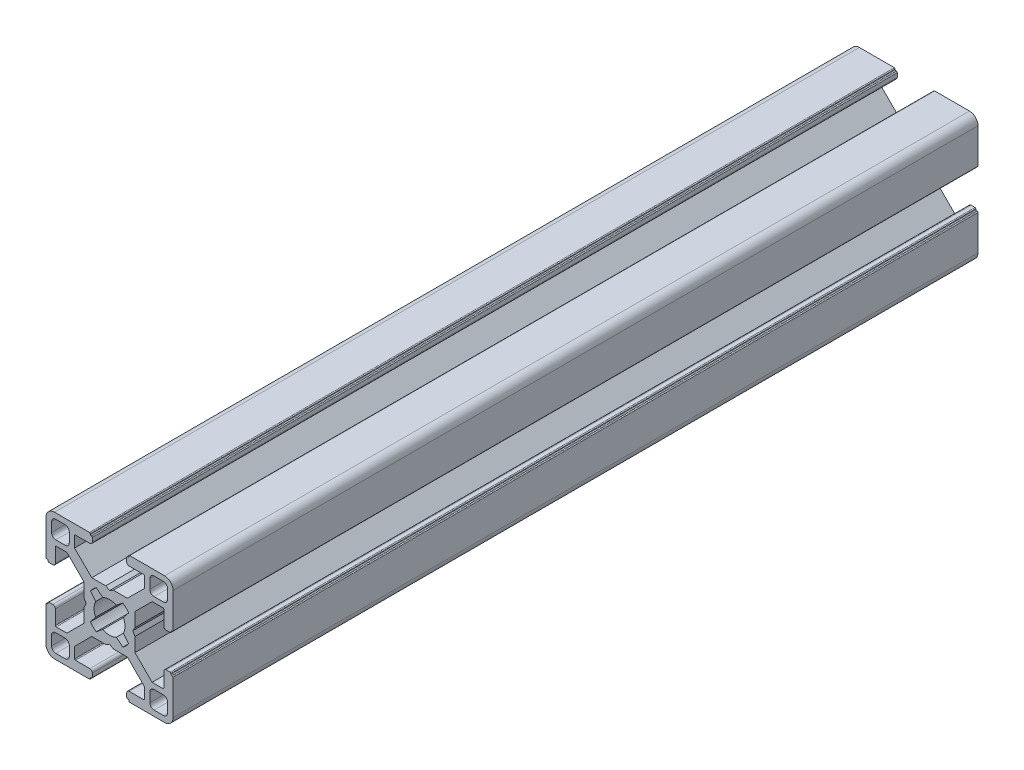
SolidWorks part; units mm, degrees
material "6061 Alloy"
ref_plane "Front" through (0, 0, 0) normal (0, 0, 1) x (1, 0, 0)
ref_plane "Top" through (0, 0, 0) normal (0, 1, 0) x (1, 0, 0)
ref_plane "Right" through (0, 0, 0) normal (1, 0, 0) x (0, 0, -1)
sketch "Sketch1" plane through (0, 0, 0) normal (0, 0, 1) x (1, 0, 0)
  line L0 (13.7, 12.7) -> (13.7, 10.5)
  line L1 (10.5, 9.5) -> (12.7, 9.5)
  line L2 (9.5, 12.7) -> (9.5, 10.5)
  line L3 (10.5, 13.7) -> (12.7, 13.7)
  line L4 (3.1359, 4.5184) -> (1.6001, 3.2806)
  line L5 (3.2806, 1.6001) -> (4.5053, 3.1547)
  line L6 (6.0045, 0.9) -> (5.4849, 0)
  line L7 (6.0045, 4.2045) -> (6.0045, 0.9)
  line L8 (0, -5.4849) -> (0.9, -6)
  line L9 (0.9, -6) -> (4.2045, -6)
  line L10 (4.2045, -6) -> (8.25, -10.05)
  line L11 (8.25, -10.05) -> (8.25, -12.6)
  line L12 (4.65, -12.8) -> (8.05, -12.8)
  line L13 (4.05, -14.3) -> (4.05, -13.4)
  line L14 (4.25, -14.5) -> (4.35, -14.5)
  line L15 (4.55, -14.8) -> (4.55, -14.7)
  line L16 (4.75, -15) -> (13, -15)
  line L17 (15, -13) -> (15, -4.75)
  line L18 (14.7, -4.55) -> (14.8, -4.55)
  line L19 (14.5, -4.35) -> (14.5, -4.25)
  line L20 (13.4, -4.05) -> (14.3, -4.05)
  line L21 (12.8, -8.05) -> (12.8, -4.65)
  line L22 (12.6, -8.25) -> (10.05, -8.25)
  line L23 (10.05, -8.25) -> (6.0045, -4.2045)
  line L24 (6.0045, -4.2045) -> (6.0045, -0.9)
  line L25 (6.0045, -0.9) -> (5.4849, 0)
  line L26 (10.05, 8.25) -> (6.0045, 4.2045)
  line L27 (12.6, 8.25) -> (10.05, 8.25)
  line L28 (12.8, 8.05) -> (12.8, 4.65)
  line L29 (13.4, 4.05) -> (14.3, 4.05)
  line L30 (14.5, 4.35) -> (14.5, 4.25)
  line L31 (14.7, 4.55) -> (14.8, 4.55)
  line L32 (15, 13) -> (15, 4.75)
  line L33 (4.75, 15) -> (13, 15)
  line L34 (4.55, 14.8) -> (4.55, 14.7)
  line L35 (4.25, 14.5) -> (4.35, 14.5)
  line L36 (4.05, 14.3) -> (4.05, 13.4)
  line L37 (4.65, 12.8) -> (8.05, 12.8)
  line L38 (8.25, 10.05) -> (8.25, 12.6)
  line L39 (4.2045, 6) -> (8.25, 10.05)
  line L40 (0.9, 6) -> (4.2045, 6)
  line L41 (0, 5.4849) -> (0.9, 6)
  line L42 (-13.7, -12.7) -> (-13.7, -10.5)
  line L43 (-10.5, -9.5) -> (-12.7, -9.5)
  line L44 (-9.5, -12.7) -> (-9.5, -10.5)
  line L45 (-10.5, -13.7) -> (-12.7, -13.7)
  line L46 (-3.1359, -4.5184) -> (-1.6001, -3.2806)
  line L47 (-3.2806, -1.6001) -> (-4.5053, -3.1547)
  line L48 (0, 5.4849) -> (-0.9, 6)
  line L49 (-0.9, 6) -> (-4.2045, 6)
  line L50 (-4.2045, 6) -> (-8.25, 10.05)
  line L51 (-8.25, 10.05) -> (-8.25, 12.6)
  line L52 (-4.65, 12.8) -> (-8.05, 12.8)
  line L53 (-4.05, 14.3) -> (-4.05, 13.4)
  line L54 (-4.25, 14.5) -> (-4.35, 14.5)
  line L55 (-4.55, 14.8) -> (-4.55, 14.7)
  line L56 (-4.75, 15) -> (-13, 15)
  line L57 (-15, 13) -> (-15, 4.75)
  line L58 (-14.7, 4.55) -> (-14.8, 4.55)
  line L59 (-14.5, 4.35) -> (-14.5, 4.25)
  line L60 (-13.4, 4.05) -> (-14.3, 4.05)
  line L61 (-12.8, 8.05) -> (-12.8, 4.65)
  line L62 (-12.6, 8.25) -> (-10.05, 8.25)
  line L63 (-10.05, 8.25) -> (-6.0045, 4.2045)
  line L64 (-6.0045, -0.9) -> (-5.4849, 0)
  line L65 (-6.0045, -4.2045) -> (-6.0045, -0.9)
  line L66 (-10.05, -8.25) -> (-6.0045, -4.2045)
  line L67 (-12.6, -8.25) -> (-10.05, -8.25)
  line L68 (-12.8, -8.05) -> (-12.8, -4.65)
  line L69 (-13.4, -4.05) -> (-14.3, -4.05)
  line L70 (-14.5, -4.35) -> (-14.5, -4.25)
  line L71 (-14.7, -4.55) -> (-14.8, -4.55)
  line L72 (-15, -13) -> (-15, -4.75)
  line L73 (-4.75, -15) -> (-13, -15)
  line L74 (-4.55, -14.8) -> (-4.55, -14.7)
  line L75 (-4.25, -14.5) -> (-4.35, -14.5)
  line L76 (-4.05, -14.3) -> (-4.05, -13.4)
  line L77 (3.2806, -1.6001) -> (4.5053, -3.1547)
  line L78 (3.1359, -4.5184) -> (1.6001, -3.2806)
  line L79 (-4.65, -12.8) -> (-8.05, -12.8)
  line L80 (-8.25, -10.05) -> (-8.25, -12.6)
  line L81 (-4.2045, -6) -> (-8.25, -10.05)
  line L82 (-0.9, -6) -> (-4.2045, -6)
  line L83 (0, -5.4849) -> (-0.9, -6)
  line L84 (10.5, -13.7) -> (12.7, -13.7)
  line L85 (9.5, -12.7) -> (9.5, -10.5)
  line L86 (10.5, -9.5) -> (12.7, -9.5)
  line L87 (13.7, -12.7) -> (13.7, -10.5)
  line L88 (-6.0045, 4.2045) -> (-6.0045, 0.9)
  line L89 (-6.0045, 0.9) -> (-5.4849, 0)
  line L90 (-3.2806, 1.6001) -> (-4.5053, 3.1547)
  line L91 (-3.1359, 4.5184) -> (-1.6001, 3.2806)
  line L92 (-10.5, 13.7) -> (-12.7, 13.7)
  line L93 (-9.5, 12.7) -> (-9.5, 10.5)
  line L94 (-10.5, 9.5) -> (-12.7, 9.5)
  line L95 (-13.7, 12.7) -> (-13.7, 10.5)
  line L96 (-23.4857, 0) -> (20.9308, 0) construction
  line L97 (0, 17.9563) -> (0, -17.361) construction
  arc A0 (13.7, 12.7) -> (12.7, 13.7) centre (12.7, 12.7) ccw
  arc A1 (12.7, 9.5) -> (13.7, 10.5) centre (12.7, 10.5) ccw
  arc A2 (9.5, 10.5) -> (10.5, 9.5) centre (10.5, 10.5) ccw
  arc A3 (10.5, 13.7) -> (9.5, 12.7) centre (10.5, 12.7) ccw
  arc A4 (1.6001, 3.2806) -> (-1.6001, 3.2806) centre (0, 0) ccw
  arc A5 (8.25, -12.6) -> (8.05, -12.8) centre (8.05, -12.6) cw
  arc A6 (4.65, -12.8) -> (4.05, -13.4) centre (4.65, -13.4) ccw
  arc A7 (4.05, -14.3) -> (4.25, -14.5) centre (4.25, -14.3) ccw
  arc A8 (4.35, -14.5) -> (4.55, -14.7) centre (4.35, -14.7) cw
  arc A9 (4.55, -14.8) -> (4.75, -15) centre (4.75, -14.8) ccw
  arc A10 (13, -15) -> (15, -13) centre (13, -13) ccw
  arc A11 (15, -4.75) -> (14.8, -4.55) centre (14.8, -4.75) ccw
  arc A12 (14.7, -4.55) -> (14.5, -4.35) centre (14.7, -4.35) cw
  arc A13 (14.5, -4.25) -> (14.3, -4.05) centre (14.3, -4.25) ccw
  arc A14 (13.4, -4.05) -> (12.8, -4.65) centre (13.4, -4.65) ccw
  arc A15 (12.8, -8.05) -> (12.6, -8.25) centre (12.6, -8.05) cw
  arc A16 (4.5053, 3.1547) -> (3.1359, 4.5184) centre (0, 0) ccw
  arc A17 (12.8, 8.05) -> (12.6, 8.25) centre (12.6, 8.05) ccw
  arc A18 (13.4, 4.05) -> (12.8, 4.65) centre (13.4, 4.65) cw
  arc A19 (14.5, 4.25) -> (14.3, 4.05) centre (14.3, 4.25) cw
  arc A20 (14.7, 4.55) -> (14.5, 4.35) centre (14.7, 4.35) ccw
  arc A21 (15, 4.75) -> (14.8, 4.55) centre (14.8, 4.75) cw
  arc A22 (13, 15) -> (15, 13) centre (13, 13) cw
  arc A23 (4.55, 14.8) -> (4.75, 15) centre (4.75, 14.8) cw
  arc A24 (4.35, 14.5) -> (4.55, 14.7) centre (4.35, 14.7) ccw
  arc A25 (4.05, 14.3) -> (4.25, 14.5) centre (4.25, 14.3) cw
  arc A26 (4.65, 12.8) -> (4.05, 13.4) centre (4.65, 13.4) cw
  arc A27 (8.25, 12.6) -> (8.05, 12.8) centre (8.05, 12.6) ccw
  arc A28 (-13.7, -12.7) -> (-12.7, -13.7) centre (-12.7, -12.7) ccw
  arc A29 (-12.7, -9.5) -> (-13.7, -10.5) centre (-12.7, -10.5) ccw
  arc A30 (-9.5, -10.5) -> (-10.5, -9.5) centre (-10.5, -10.5) ccw
  arc A31 (-10.5, -13.7) -> (-9.5, -12.7) centre (-10.5, -12.7) ccw
  arc A32 (-4.5053, -3.1547) -> (-3.1359, -4.5184) centre (0, 0) ccw
  arc A33 (-3.2806, 1.6001) -> (-3.2806, -1.6001) centre (0, 0) ccw
  arc A34 (-8.25, 12.6) -> (-8.05, 12.8) centre (-8.05, 12.6) cw
  arc A35 (-4.65, 12.8) -> (-4.05, 13.4) centre (-4.65, 13.4) ccw
  arc A36 (-4.05, 14.3) -> (-4.25, 14.5) centre (-4.25, 14.3) ccw
  arc A37 (-4.35, 14.5) -> (-4.55, 14.7) centre (-4.35, 14.7) cw
  arc A38 (-4.55, 14.8) -> (-4.75, 15) centre (-4.75, 14.8) ccw
  arc A39 (-13, 15) -> (-15, 13) centre (-13, 13) ccw
  arc A40 (-15, 4.75) -> (-14.8, 4.55) centre (-14.8, 4.75) ccw
  arc A41 (-14.7, 4.55) -> (-14.5, 4.35) centre (-14.7, 4.35) cw
  arc A42 (-14.5, 4.25) -> (-14.3, 4.05) centre (-14.3, 4.25) ccw
  arc A43 (-13.4, 4.05) -> (-12.8, 4.65) centre (-13.4, 4.65) ccw
  arc A44 (-12.8, 8.05) -> (-12.6, 8.25) centre (-12.6, 8.05) cw
  arc A45 (-4.5053, 3.1547) -> (-3.1359, 4.5184) centre (0, 0) cw
  arc A46 (-12.8, -8.05) -> (-12.6, -8.25) centre (-12.6, -8.05) ccw
  arc A47 (-13.4, -4.05) -> (-12.8, -4.65) centre (-13.4, -4.65) cw
  arc A48 (-14.5, -4.25) -> (-14.3, -4.05) centre (-14.3, -4.25) cw
  arc A49 (3.2806, 1.6001) -> (3.2806, -1.6001) centre (0, 0) cw
  arc A50 (4.5053, -3.1547) -> (3.1359, -4.5184) centre (0, 0) cw
  arc A51 (1.6001, -3.2806) -> (-1.6001, -3.2806) centre (0, 0) cw
  arc A52 (-14.7, -4.55) -> (-14.5, -4.35) centre (-14.7, -4.35) ccw
  arc A53 (-15, -4.75) -> (-14.8, -4.55) centre (-14.8, -4.75) cw
  arc A54 (-13, -15) -> (-15, -13) centre (-13, -13) cw
  arc A55 (-4.55, -14.8) -> (-4.75, -15) centre (-4.75, -14.8) cw
  arc A56 (10.5, -13.7) -> (9.5, -12.7) centre (10.5, -12.7) cw
  arc A57 (9.5, -10.5) -> (10.5, -9.5) centre (10.5, -10.5) cw
  arc A58 (12.7, -9.5) -> (13.7, -10.5) centre (12.7, -10.5) cw
  arc A59 (13.7, -12.7) -> (12.7, -13.7) centre (12.7, -12.7) cw
  arc A60 (-4.35, -14.5) -> (-4.55, -14.7) centre (-4.35, -14.7) ccw
  arc A61 (-4.05, -14.3) -> (-4.25, -14.5) centre (-4.25, -14.3) cw
  arc A62 (-4.65, -12.8) -> (-4.05, -13.4) centre (-4.65, -13.4) cw
  arc A63 (-8.25, -12.6) -> (-8.05, -12.8) centre (-8.05, -12.6) ccw
  arc A64 (-10.5, 13.7) -> (-9.5, 12.7) centre (-10.5, 12.7) cw
  arc A65 (-9.5, 10.5) -> (-10.5, 9.5) centre (-10.5, 10.5) cw
  arc A66 (-12.7, 9.5) -> (-13.7, 10.5) centre (-12.7, 10.5) cw
  arc A67 (-13.7, 12.7) -> (-12.7, 13.7) centre (-12.7, 12.7) cw
  point P81 (15, 15)
  point P82 (0, 15)
  point P203 (0, -15)
  point P204 (15, -15)
  point P206 (0, 0)
  point P207 (15, 0)
  point P219 (-15, 0)
  point P220 (-15, -15)
  point P221 (-15, 15)
extrude "Base-Extrude" add sketch "Sketch1" against normal blind 190
sketch "草图2" plane through (15, 0, 0) normal (1, 0, 0) x (0, 0, -1)
  line L0 (0, 15) -> (30, -15)
  line L1 (190, -15) -> (0, -15) construction
  line L2 (0, 4.75) -> (0, 13) construction
  line L3 (0, 15) -> (0, -15)
  line L4 (0, -15) -> (30, -15)
  line L5 (-13.0087, 11.9543) -> (-11.263, 12.8943)
  dimension "D1" = 45
